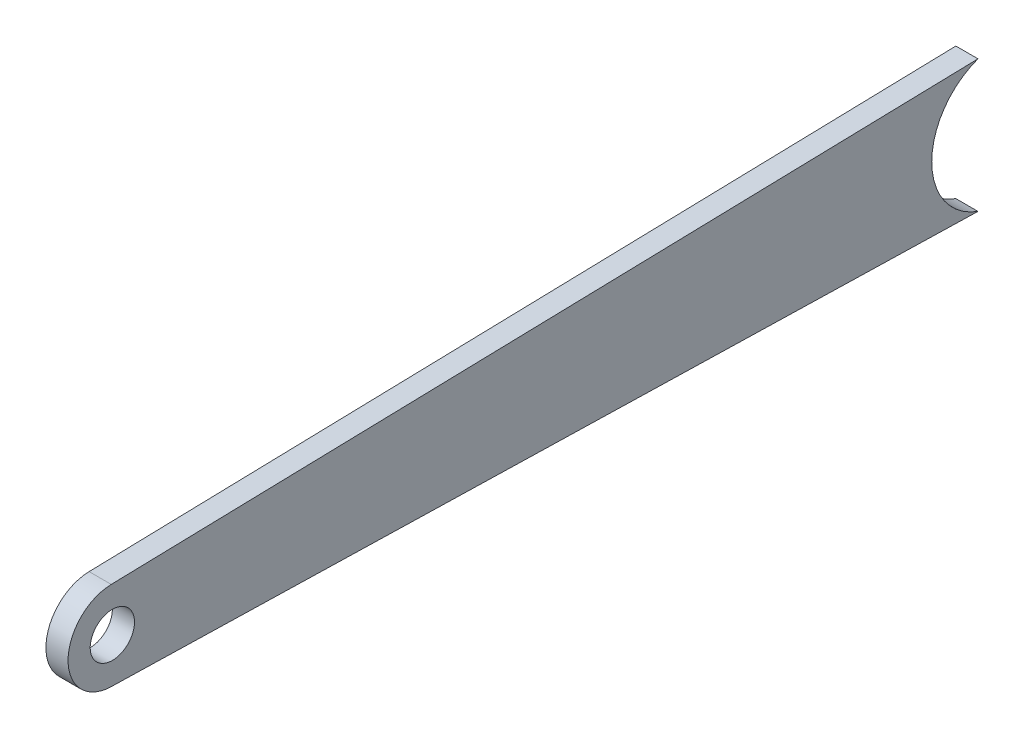
SolidWorks part; units mm, degrees
ref_plane "Front Plane" through (0, 0, 0) normal (1, 0, 0) x (0, 1, 0)
ref_plane "Top Plane" through (0, 0, 0) normal (0, 0, 1) x (0, 1, 0)
ref_plane "Right Plane" through (0, 0, 0) normal (0, 1, 0) x (-1, 0, 0)
sketch "Sketch1" plane through (0, 0, 0) normal (1, 0, 0) x (0, 1, 0)
  line L0 (0, 15.875) -> (0, 200.875) construction
  line L1 (9.9968, 201.1264) -> (14.9176, 5.4296)
  line L2 (-9.9968, 201.1264) -> (-14.9176, 5.4296)
  line L3 (0, 0) -> (15.875, 0) construction
  line L4 (0, 0) -> (14.9176, 5.4296) construction
  circle A0 centre (0, 0) radius 15.875
  circle A1 centre (0, 200.875) radius 5
  arc A2 (9.9968, 201.1264) -> (-9.9968, 201.1264) centre (0, 200.875) ccw
  arc A3 (-9.9968, 201.1264) -> (0, 190.875) centre (0, 200.875) ccw construction
  arc A4 (0, 190.875) -> (9.9968, 201.1264) centre (0, 200.875) ccw construction
  point P11 (0, 0)
  point P14 (0, 0)
  point P15 (0, 0)
  dimension "D1" = 31.75
  dimension "D3" = 10
  dimension "D4" = 20
  dimension "D5" = 20
  dimension "D2" = 185
extrude "Boss-Extrude1" add sketch "Sketch1" along normal mid plane 5 contours L1 A2 L2 A0 A1
